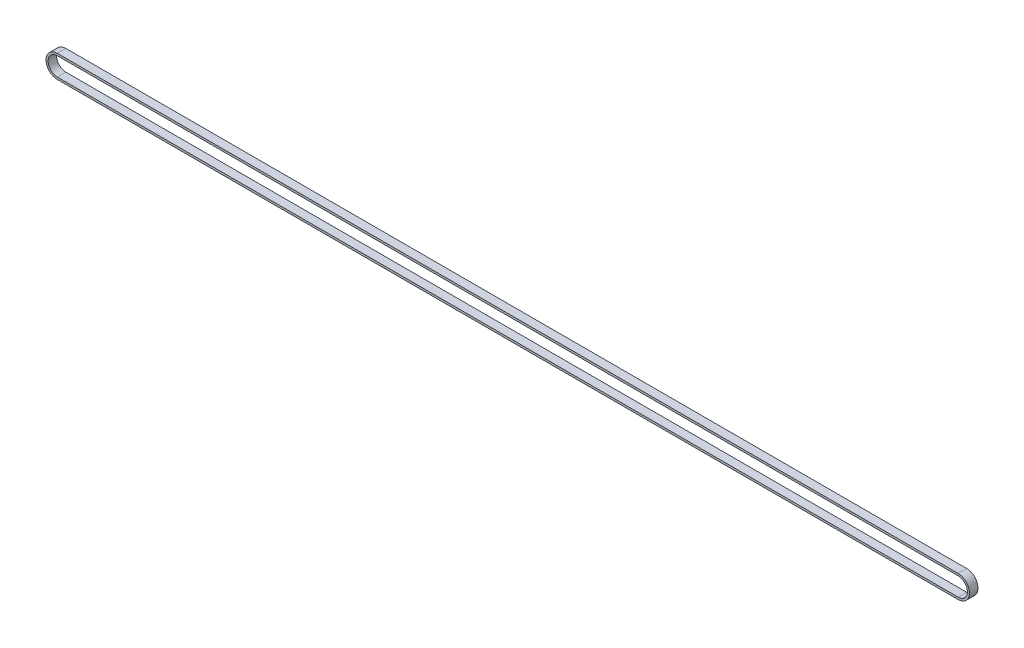
SolidWorks part; units mm, degrees
material "Rubber"
ref_plane "Front Plane" through (0, 0, 0) normal (0, 0, 1) x (1, 0, 0)
ref_plane "Top Plane" through (0, 0, 0) normal (0, 1, 0) x (1, 0, 0)
ref_plane "Right Plane" through (0, 0, 0) normal (1, 0, 0) x (0, 0, -1)
sketch "Sketch1" plane through (0, 0, 0) normal (0, 0, 1) x (1, 0, 0)
  line L0 (317.5, 0) -> (-317.5, 0)
  line L4 (-317.5, -14) -> (317.5, -14)
  arc A0 (-317.5, 0) -> (-317.5, -14) centre (-317.5, -7) ccw
  arc A1 (317.5, -14) -> (317.5, 0) centre (317.5, -7) ccw
  dimension "D1" = 7
  dimension "D2" = 635
extrude "Extrude-Thin1" add sketch "Sketch1" along normal mid plane 6 thin
